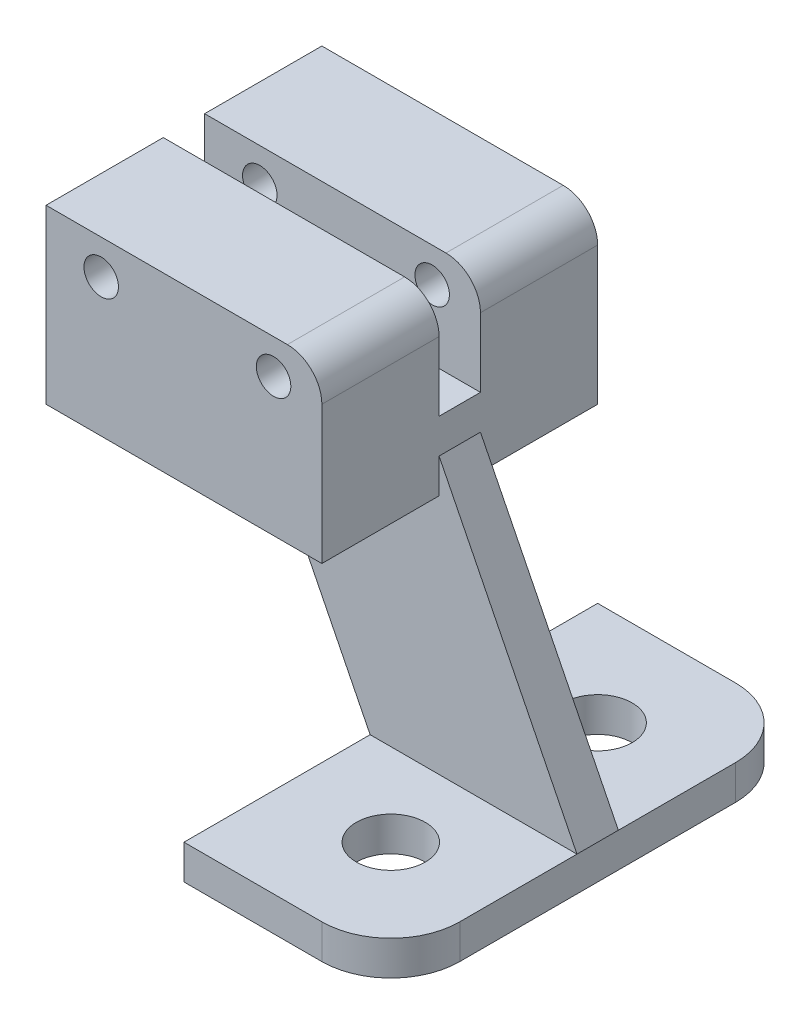
SolidWorks part; units mm, degrees
ref_plane "Front Plane" through (0, 0, 0) normal (0, 0, 1) x (1, 0, 0)
ref_plane "Top Plane" through (0, 0, 0) normal (0, 1, 0) x (1, 0, 0)
ref_plane "Right Plane" through (0, 0, 0) normal (1, 0, 0) x (0, 0, -1)
sketch "Sketch1" plane through (0, 0, 0) normal (0, 0, 1) x (1, 0, 0)
  line L0 (63.5649, 0) -> (-111.0747, 0)
  line L1 (63.5649, 14.5806) -> (33.5649, 14.5806)
  line L2 (33.5649, 14.5806) -> (33.5649, 19.5806)
  line L3 (33.5649, 19.5806) -> (63.5649, 19.5806)
  line L4 (63.5649, 19.5806) -> (63.5649, 14.5806)
extrude "Boss-Extrude1" add sketch "Sketch1" along normal blind 60 contours L4 L3 L2 L1
fillet "Fillet1" radius 10 2 edges at (63.5649, 17.0806, 0) (63.5649, 17.0806, 60)
sketch "Sketch2" plane through (0, 19.5806, 0) normal (0, 1, 0) x (1, 0, 0)
  point P7 (48.5649, -15)
  point P8 (48.5649, -45)
hole_wizard "Ø10.0 (10) Diameter Hole1" positions "3DSketch1" profile "Sketch3" hole size "Ø10.0" standard "DIN" end condition through all
sketch3d "3DSketch1"
  point P0 (48.5649, 19.5806, 15)
  point P3 (48.5649, 19.5806, 45)
sketch "Sketch3" plane through (48.5649, 19.5806, 15) normal (1, 0, 0) x (0, 0, 1)
  line L0 (0, 0) -> (0, 5)
  line L1 (0, 5) -> (5, 5)
  line L2 (5, 5) -> (5, 0)
  line L5 (5, 0) -> (0, 0)
  line L11 (0, -6.35) -> (0, 107.95) construction
  dimension "Thru Hole Dia." = 10
  dimension "Thru Hole Depth" = 5
sketch "Sketch4" plane through (0, 19.5806, 0) normal (0, 1, 0) x (1, 0, 0)
  line L0 (63.5649, -33) -> (63.5649, -27)
  line L1 (63.5649, -50) -> (63.5649, -10) construction
  line L5 (63.5649, -33) -> (13.5649, -33)
  line L6 (13.5649, -33) -> (13.5649, -27)
  line L7 (13.5649, -27) -> (63.5649, -27)
extrude "Boss-Extrude4" add sketch "Sketch4" along normal blind 40
sketch "Sketch10" plane through (0, 0, 33) normal (0, 0, 1) x (1, 0, 0)
  line L0 (33.5649, 19.5806) -> (13.5649, 59.5806)
  line L2 (13.5649, 59.5806) -> (63.5649, 59.5806) construction
  line L3 (63.5649, 19.5806) -> (43.5649, 59.5806)
  line M3 (13.5649, 19.5806) -> (33.5649, 19.5806)
  line M5 (63.5649, 19.5806) -> (63.5649, 59.5806)
  line M6 (63.5649, 59.5806) -> (13.5649, 59.5806)
  line M7 (13.5649, 59.5806) -> (13.5649, 19.5806)
extrude "Cut-Extrude3" cut sketch "Sketch10" against normal blind 40 contours L0 M3 M7 | L3 M5 M6
sketch "Sketch11" plane through (0, 59.5806, 0) normal (0, 1, 0) x (1, 0, 0)
  line L0 (43.5649, -30) -> (43.5649, -10)
  line L1 (43.5649, -27) -> (43.5649, -33) construction
  line L2 (43.5649, -10) -> (3.5649, -10)
  line L3 (3.5649, -10) -> (3.5649, -50)
  line L4 (3.5649, -50) -> (43.5649, -50)
  line L5 (43.5649, -50) -> (43.5649, -30)
extrude "Boss-Extrude5" add sketch "Sketch11" along normal blind 20 and the other way blind 5
sketch "Sketch12" plane through (43.5649, 0, 0) normal (1, 0, 0) x (0, 0, -1)
  line L1 (-50, 79.5806) -> (-10, 79.5806) construction
  line L4 (-30, 64.5806) -> (-25, 64.5806)
  line L5 (-30, 64.5806) -> (-35, 64.5806)
  line L6 (-35, 64.5806) -> (-35, 79.5806)
  line L7 (-35, 79.5806) -> (-25, 79.5806)
  line L8 (-25, 79.5806) -> (-25, 64.5806)
sketch "Sketch13" plane through (0, 0, 50) normal (0, 0, 1) x (1, 0, 0)
  point P1 (36.5649, 74.5806)
  point P7 (11.5649, 74.5806)
hole_wizard "Ø5.0 (5) Diameter Hole1" positions "3DSketch2" profile "Sketch14" hole size "Ø5.0" standard "DIN" end condition through all
sketch3d "3DSketch2"
  point P0 (36.5649, 74.5806, 50)
  point P3 (11.5649, 74.5806, 50)
sketch "Sketch14" plane through (36.5649, 74.5806, 50) normal (1, 0, 0) x (0, -1, 0)
  line L0 (0, 0) -> (0, 50)
  line L1 (0, 50) -> (2.5, 50)
  line L2 (2.5, 50) -> (2.5, 0)
  line L5 (2.5, 0) -> (0, 0)
  line L11 (0, -6.35) -> (0, 107.95) construction
  dimension "Thru Hole Dia." = 5
  dimension "Thru Hole Depth" = 50
sketch "Sketch15" plane through (43.5649, 0, 0) normal (1, 0, 0) x (0, 0, -1)
  line L0 (-30, 64.5806) -> (-27, 64.5806)
  line L1 (-30, 64.5806) -> (-25, 64.5806) construction
  line L2 (-30, 64.5806) -> (-33, 64.5806)
  line L3 (-30, 64.5806) -> (-35, 64.5806) construction
  line L4 (-33, 64.5806) -> (-33, 79.5806)
  line L5 (-35, 79.5806) -> (-25, 79.5806) construction
  line L6 (-33, 79.5806) -> (-27, 79.5806)
  line L7 (-27, 79.5806) -> (-27, 64.5806)
extrude "Cut-Extrude4" cut sketch "Sketch15" against normal through all
fillet "Fillet2" radius 5 1 edges at (43.5649, 79.5806, 41.5)
fillet "Fillet3" radius 5 1 edges at (43.5649, 79.5806, 18.5)
